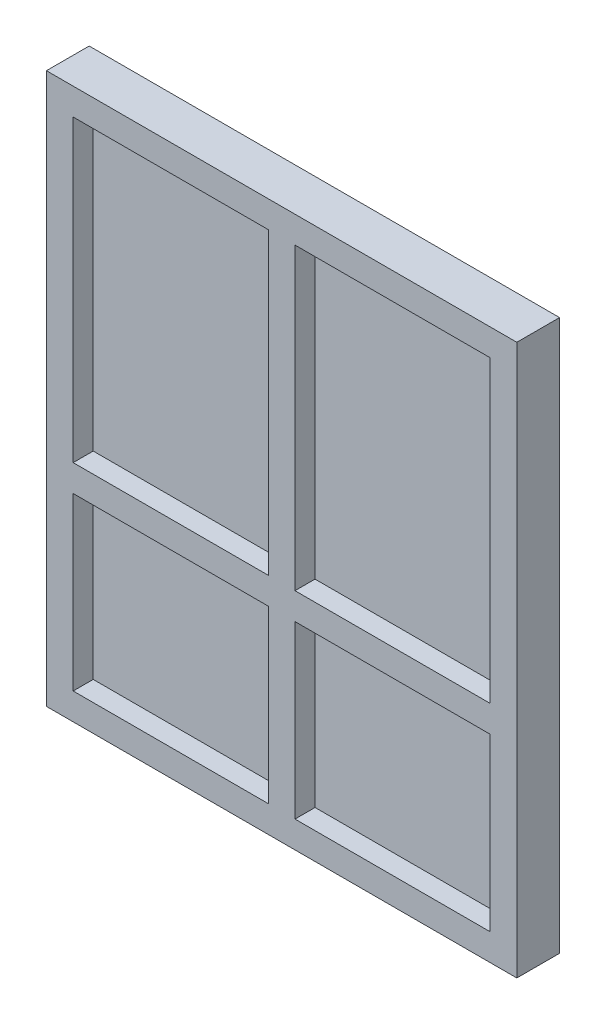
SolidWorks part; units mm, degrees
ref_plane "Спереди" through (0, 0, 0) normal (0, 0, 1) x (1, 0, 0)
ref_plane "Сверху" through (0, 0, 0) normal (0, 1, 0) x (1, 0, 0)
ref_plane "Справа" through (0, 0, 0) normal (1, 0, 0) x (0, 0, -1)
other "Configuration Table"
sketch "Эскиз1" plane through (0, 0, 0) normal (0, 0, 1) x (1, 0, 0)
  line L0 (830, 740) -> (930, 740) construction
  line L1 (0, 2060) -> (1760, 2060)
  line L2 (0, 2060) -> (0, 0)
  line L3 (0, 0) -> (1760, 0)
  line L4 (1760, 2060) -> (1760, 0)
  line L5 (100, 1960) -> (830, 1960)
  line L6 (100, 1960) -> (100, 840)
  line L7 (100, 840) -> (830, 840)
  line L8 (830, 1960) -> (830, 840)
  line L9 (100, 740) -> (830, 740)
  line L10 (100, 740) -> (100, 100)
  line L11 (100, 100) -> (830, 100)
  line L12 (830, 740) -> (830, 100)
  line L13 (930, 1960) -> (1660, 1960)
  line L14 (930, 1960) -> (930, 840)
  line L15 (930, 840) -> (1660, 840)
  line L16 (1660, 1960) -> (1660, 840)
  line L17 (930, 740) -> (1660, 740)
  line L18 (930, 740) -> (930, 100)
  line L19 (930, 100) -> (1660, 100)
  line L20 (1660, 740) -> (1660, 100)
  line L21 (930, 740) -> (930, 840) construction
  line L22 (1660, 740) -> (1660, 840) construction
  line L23 (100, 740) -> (100, 840) construction
  line L24 (830, 740) -> (830, 840) construction
  line L25 (830, 840) -> (930, 840) construction
  line L26 (830, 1960) -> (930, 1960) construction
  line L27 (830, 100) -> (930, 100) construction
  line L28 (100, 1960) -> (100, 2060) construction
  line L29 (100, 2060) -> (100, 1960) construction
  line L30 (100, 100) -> (100, 0) construction
  line L31 (100, 1960) -> (0, 1960) construction
  line L32 (1660, 1960) -> (1760, 1960) construction
  dimension "D1" = 100
  dimension "D2" = 1120
  dimension "D3" = 1760
  dimension "D4" = 2060
extrude "Бобышка-Вытянуть1" add sketch "Эскиз1" along normal mid plane 160
ref_plane "Плоскость1" through (0, 0, 0) normal (0, 0, 1) x (1, 0, 0)
sketch "Эскиз2" plane through (0, 0, 0) normal (0, 0, 1) x (1, 0, 0)
  line L1 (100, 1960) -> (1660, 1960)
  line L2 (100, 1960) -> (100, 100)
  line L3 (100, 100) -> (1660, 100)
  line L4 (1660, 1960) -> (1660, 100)
extrude "Бобышка-Вытянуть2" add sketch "Эскиз2" along normal mid plane 10 separate body
